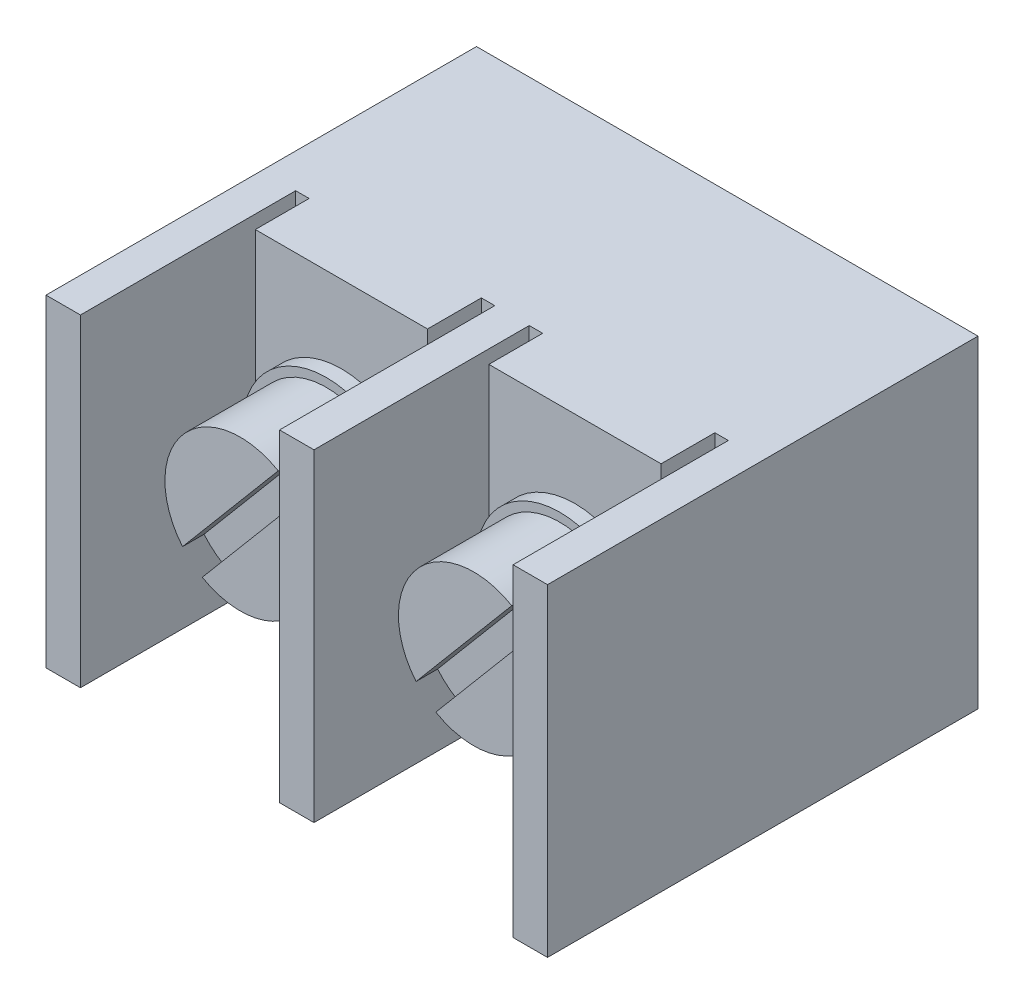
SolidWorks part; units mm, degrees
ref_plane "Спереди" through (0, 0, 0) normal (0, 0, 1) x (1, 0, 0)
ref_plane "Сверху" through (0, 0, 0) normal (0, 1, 0) x (1, 0, 0)
ref_plane "Справа" through (0, 0, 0) normal (1, 0, 0) x (0, 0, -1)
sketch "Эскиз1" plane through (0, 0, 0) normal (0, 0, 1) x (1, 0, 0)
  line L0 (-47.9787, 0) -> (44.4324, 0) construction
  line L1 (0, 0) -> (0, 38.9044) construction
  line L2 (-22.5, -7.5) -> (22.5, -7.5)
  line L3 (-22.5, -7.5) -> (-22.5, 7.5)
  line L4 (-22.5, 7.5) -> (22.5, 7.5)
  line L5 (22.5, -7.5) -> (22.5, 7.5)
  dimension "D1" = 15
  dimension "D2" = 45
extrude "Вытянуть1" add sketch "Эскиз1" along normal blind 10
sketch "Эскиз2" plane through (0, 0, 10) normal (0, 0, 1) x (1, 0, 0)
  line L0 (22.5, 7.5) -> (-22.5, 7.5) construction
  line L1 (-22.5, -7.5) -> (-20.9, -7.5)
  line L2 (-22.5, -7.5) -> (-22.5, 7.5)
  line L3 (-22.5, 7.5) -> (-20.9, 7.5)
  line L4 (-20.9, -7.5) -> (-20.9, 7.5)
  line L5 (0, 13.212) -> (0, -10.8914) construction
  line L6 (-22.5, -7.5) -> (22.5, -7.5) construction
  line L7 (-11.65, -7.5) -> (-10.05, -7.5)
  line L8 (-11.65, -7.5) -> (-11.65, 7.5)
  line L9 (-11.65, 7.5) -> (-10.05, 7.5)
  line L10 (-10.05, -7.5) -> (-10.05, 7.5)
  line L11 (-10.85, 8.3866) -> (-10.85, -8.2377) construction
  line L12 (-0.8, -7.5) -> (0.8, -7.5)
  line L13 (-0.8, -7.5) -> (-0.8, 7.5)
  line L14 (-0.8, 7.5) -> (0.8, 7.5)
  line L15 (0.8, -7.5) -> (0.8, 7.5)
  line L16 (10.05, -7.5) -> (10.05, 7.5)
  line L17 (11.65, 7.5) -> (10.05, 7.5)
  line L18 (11.65, -7.5) -> (11.65, 7.5)
  line L19 (11.65, -7.5) -> (10.05, -7.5)
  line L20 (20.9, -7.5) -> (20.9, 7.5)
  line L21 (22.5, 7.5) -> (20.9, 7.5)
  line L22 (22.5, -7.5) -> (22.5, 7.5)
  line L23 (22.5, -7.5) -> (20.9, -7.5)
  dimension "D1" = 1.6
  dimension "D2" = 10.85
extrude "Вытянуть2" add sketch "Эскиз2" along normal blind 10
sketch "Эскиз3" plane through (0, 0, 10) normal (0, 0, 1) x (1, 0, 0)
  line L0 (-16.275, 10.8914) -> (-16.275, -9.6255) construction
  line L1 (-24.3143, 0) -> (23.7342, 0) construction
  line L3 (-11.65, 7.5) -> (-11.65, -7.5) construction
  line L4 (-20.9, -7.5) -> (-20.9, 7.5) construction
  line L5 (-20.9, -7.5) -> (-11.65, -7.5) construction
  line L6 (-20.275, -7.5) -> (-12.275, -7.5)
  line L7 (-20.275, -7.5) -> (-20.275, 7.5)
  line L8 (-20.275, 7.5) -> (-12.275, 7.5)
  line L9 (-12.275, -7.5) -> (-12.275, 7.5)
  line L10 (-11.65, 7.5) -> (-20.9, 7.5) construction
  line L11 (-9.425, -7.5) -> (-1.425, -7.5)
  line L12 (-9.425, -7.5) -> (-9.425, 7.5)
  line L13 (-9.425, 7.5) -> (-1.425, 7.5)
  line L14 (-1.425, -7.5) -> (-1.425, 7.5)
  line L15 (1.425, -7.5) -> (9.425, -7.5)
  line L16 (1.425, -7.5) -> (1.425, 7.5)
  line L17 (1.425, 7.5) -> (9.425, 7.5)
  line L18 (9.425, -7.5) -> (9.425, 7.5)
  line L19 (12.275, -7.5) -> (20.275, -7.5)
  line L20 (12.275, -7.5) -> (12.275, 7.5)
  line L21 (12.275, 7.5) -> (20.275, 7.5)
  line L22 (20.275, -7.5) -> (20.275, 7.5)
  dimension "D1" = 8
extrude "Вытянуть3" add sketch "Эскиз3" along normal blind 2.5
sketch "Эскиз4" plane through (0, 0, 12.5) normal (0, 0, 1) x (1, 0, 0)
  line L0 (-24.2616, 0) -> (23.4177, 0) construction
  line L1 (-16.275, 10.7331) -> (-16.275, -8.9399) construction
  line L2 (-20.275, 7.5) -> (-20.275, -7.5) construction
  line L3 (-12.275, -7.5) -> (-12.275, 7.5) construction
  circle A0 centre (-16.275, 0) radius 3.9
  circle A1 centre (-5.425, 0) radius 3.9
  circle A2 centre (5.425, 0) radius 3.9
  circle A3 centre (16.275, 0) radius 3.9
  circle A42 centre (70.525, 0) radius 3.9 [skipped]
  circle A43 centre (81.375, 0) radius 3.9 [skipped]
  circle A44 centre (92.225, 0) radius 3.9 [skipped]
  circle A45 centre (103.075, 0) radius 3.9 [skipped]
  circle A46 centre (113.925, 0) radius 3.9 [skipped]
  circle A47 centre (124.775, 0) radius 3.9 [skipped]
  circle A48 centre (135.625, 0) radius 3.9 [skipped]
  circle A49 centre (146.475, 0) radius 3.9 [skipped]
  circle A50 centre (157.325, 0) radius 3.9 [skipped]
  circle A51 centre (168.175, 0) radius 3.9 [skipped]
  circle A52 centre (179.025, 0) radius 3.9 [skipped]
  circle A53 centre (189.875, 0) radius 3.9 [skipped]
  circle A54 centre (200.725, 0) radius 3.9 [skipped]
  circle A55 centre (211.575, 0) radius 3.9 [skipped]
  circle A56 centre (222.425, 0) radius 3.9 [skipped]
  circle A57 centre (233.275, 0) radius 3.9 [skipped]
  circle A58 centre (244.125, 0) radius 3.9 [skipped]
  circle A59 centre (254.975, 0) radius 3.9 [skipped]
  circle A60 centre (265.825, 0) radius 3.9 [skipped]
  circle A61 centre (276.675, 0) radius 3.9 [skipped]
  circle A62 centre (287.525, 0) radius 3.9 [skipped]
  circle A63 centre (298.375, 0) radius 3.9 [skipped]
  circle A64 centre (309.225, 0) radius 3.9 [skipped]
  circle A65 centre (320.075, 0) radius 3.9 [skipped]
  circle A66 centre (330.925, 0) radius 3.9 [skipped]
  circle A67 centre (341.775, 0) radius 3.9 [skipped]
  circle A68 centre (352.625, 0) radius 3.9 [skipped]
  circle A69 centre (363.475, 0) radius 3.9 [skipped]
  circle A70 centre (374.325, 0) radius 3.9 [skipped]
  circle A71 centre (385.175, 0) radius 3.9 [skipped]
  circle A72 centre (396.025, 0) radius 3.9 [skipped]
  circle A73 centre (406.875, 0) radius 3.9 [skipped]
  circle A74 centre (417.725, 0) radius 3.9 [skipped]
  circle A75 centre (428.575, 0) radius 3.9 [skipped]
  circle A76 centre (27.125, 0) radius 3.9 [skipped]
  circle A77 centre (37.975, 0) radius 3.9 [skipped]
  circle A78 centre (48.825, 0) radius 3.9 [skipped]
  circle A79 centre (59.675, 0) radius 3.9 [skipped]
  dimension "D1" = 7.8
extrude "Вытянуть4" add sketch "Эскиз4" along normal blind 0.7
sketch "Эскиз6" plane through (0, 0, 13.2) normal (0, 0, 1) x (1, 0, 0)
  circle A0 centre (-16.275, 0) radius 3.5
  circle A1 centre (-16.275, 0) radius 3.9 construction
  circle A2 centre (-5.425, 0) radius 3.5
  circle A3 centre (5.425, 0) radius 3.5
  circle A4 centre (16.275, 0) radius 3.5
  dimension "D1" = 7
extrude "Вытянуть5" add sketch "Эскиз6" along normal blind 4
sketch "Эскиз7" plane through (0, 0, 17.2) normal (0, 0, 1) x (1, 0, 0)
  line L0 (-16.275, 0) -> (-11.0149, 0.4476) construction
  line L1 (-16.275, 0) -> (-12.9483, 3.9455) construction
  line L2 (-14.511, 3.0229) -> (-18.9564, -2.2494)
  line L3 (-13.5936, 2.2494) -> (-18.039, -3.0229)
  line L4 (-3.661, 3.0229) -> (-8.1064, -2.2494)
  line L5 (-2.7436, 2.2494) -> (-7.189, -3.0229)
  line L6 (7.189, 3.0229) -> (2.7436, -2.2494)
  line L7 (8.1064, 2.2494) -> (3.661, -3.0229)
  line L8 (18.039, 3.0229) -> (13.5936, -2.2494)
  line L9 (18.9564, 2.2494) -> (14.511, -3.0229)
  circle A0 centre (-16.275, 0) radius 3.5 construction
  arc A1 (-13.5936, 2.2494) -> (-14.511, 3.0229) centre (-16.275, 0) ccw
  arc A2 (-18.9564, -2.2494) -> (-18.039, -3.0229) centre (-16.275, 0) ccw
  arc A3 (-2.7436, 2.2494) -> (-3.661, 3.0229) centre (-5.425, 0) ccw
  arc A4 (-8.1064, -2.2494) -> (-7.189, -3.0229) centre (-5.425, 0) ccw
  arc A5 (8.1064, 2.2494) -> (7.189, 3.0229) centre (5.425, 0) ccw
  arc A6 (2.7436, -2.2494) -> (3.661, -3.0229) centre (5.425, 0) ccw
  arc A7 (18.9564, 2.2494) -> (18.039, 3.0229) centre (16.275, 0) ccw
  arc A8 (13.5936, -2.2494) -> (14.511, -3.0229) centre (16.275, 0) ccw
  dimension "D1" = 45
  dimension "D2" = 1.2
extrude "Вырез-Вытянуть1" cut sketch "Эскиз7" against normal blind 1
sketch "Эскиз8" plane through (0, 0, 0) normal (0, 0, -1) x (-1, 0, 0)
  line L0 (-23.7342, 0) -> (23.7342, 0) construction
  line L1 (0, 12.8956) -> (0, -12.4209) construction
  circle A0 centre (-5, 0) radius 0.85
  circle A1 centre (5, 0) radius 0.85
  circle A2 centre (15, 0) radius 0.85
  circle A3 centre (-15, 0) radius 0.85
  dimension "D1" = 10
  dimension "D2" = 30
  dimension "D3" = 1.7
extrude "Вытянуть6" add sketch "Эскиз8" along normal blind 2.5
sketch "Эскиз9" plane through (22.5, 0, 0) normal (1, 0, 0) x (0, 0, -1)
  line L1 (-23.0597, -11.7187) -> (5.2849, -11.7187)
  line L2 (-23.0597, -11.7187) -> (-23.0597, 12.3075)
  line L3 (-23.0597, 12.3075) -> (5.2849, 12.3075)
  line L4 (5.2849, -11.7187) -> (5.2849, 12.3075)
extrude "Вырез-Вытянуть2" cut sketch "Эскиз9" against normal up to surface (21.7 mm away) up to face at (0.8, 0, 15)
